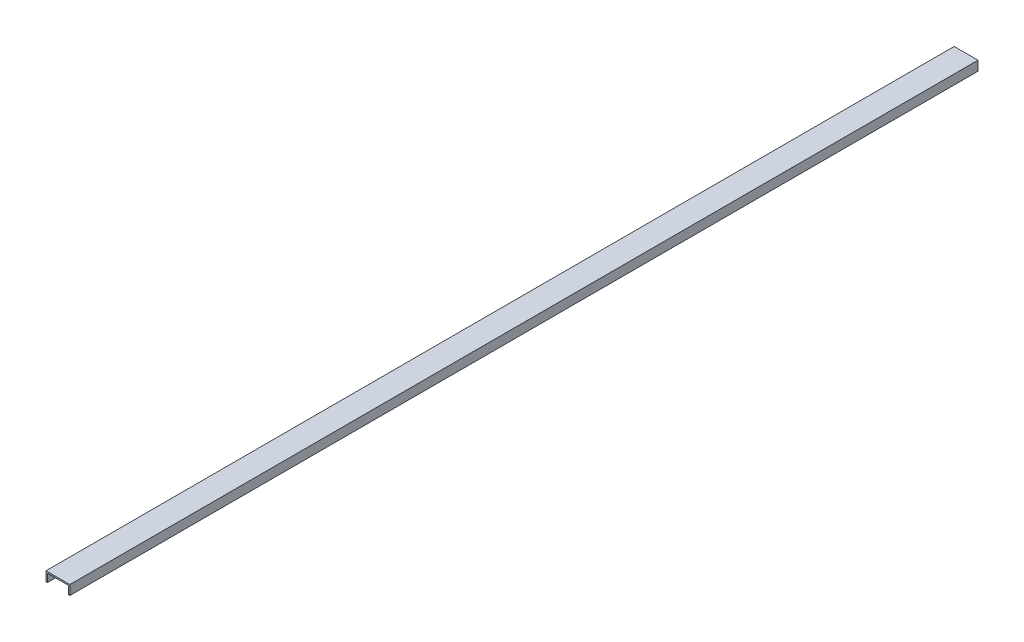
SolidWorks part; units mm, degrees
ref_plane "Front Plane" through (0, 0, 0) normal (0, 0, 1) x (1, 0, 0)
ref_plane "Top Plane" through (0, 0, 0) normal (0, 1, 0) x (1, 0, 0)
ref_plane "Right Plane" through (0, 0, 0) normal (1, 0, 0) x (0, 0, -1)
sketch "Sketch1" plane through (0, 0, 0) normal (0, 0, 1) x (1, 0, 0)
  line L0 (0, 0) -> (0, 20)
  line L1 (0, 20) -> (50, 20)
  line L2 (50, 20) -> (50, 0)
  line L3 (50, 0) -> (47, 0)
  line L4 (47, 0) -> (47, 17)
  line L5 (47, 17) -> (3, 17)
  line L6 (3, 17) -> (3, 0)
  line L7 (3, 0) -> (0, 0)
  dimension "D1" = 50
  dimension "D2" = 20
  dimension "D3" = 3
  dimension "D4" = 3
extrude "Boss-Extrude1" add sketch "Sketch1" along normal blind 1785
sketch "Sketch2" plane through (0, 0, 1785) normal (0, 0, 1) x (1, 0, 0)
  line L0 (0, 0) -> (0, 20)
  line L1 (0, 20) -> (50, 20)
  line L2 (50, 20) -> (50, 0)
  line L3 (50, 0) -> (47, 0)
  line L4 (47, 0) -> (47, 17)
  line L5 (47, 17) -> (3, 17)
  line L6 (3, 17) -> (3, 0)
  line L7 (3, 0) -> (0, 0)
extrude "R" add sketch "Sketch2" along normal blind 60
sketch "Sketch3" plane through (0, 0, 0) normal (0, 0, -1) x (-1, 0, 0)
  line L0 (-50, 0) -> (-50, 20)
  line L1 (-50, 20) -> (0, 20)
  line L2 (0, 20) -> (0, 0)
  line L3 (0, 0) -> (-3, 0)
  line L4 (-3, 0) -> (-3, 17)
  line L5 (-3, 17) -> (-47, 17)
  line L6 (-47, 17) -> (-47, 0)
  line L7 (-47, 0) -> (-50, 0)
extrude "L" add sketch "Sketch3" along normal blind 60
equation "\"boxWidth\"=1930.0"
equation "\"D1@Boss-Extrude1\"= \"boxWidth\" - 70 - 70 - 5"
equation "\"start\"=700.0"
equation "\"CarBeamWidth\"=700.0"
equation "\"WheelWidth\"=650.0"
equation "\"Wheel_FrontBoxDistance\"=1390.0"
equation "\"boxLength\"=5100.0"
equation "\"MetalSheet_3mm_length\"=5030.0"
equation "\"MetalSheet_3mm_width\"=1923.0"
equation "\"MetalSheet_3mm_FloorCut_L_length\"=1764.0"
equation "\"MetalSheet_3mm_FloorCut_L_disdance\"=1665.0"
equation "\"MetalSheet_3mm_FloorCut_R_length\"=1764.0"
equation "\"MetalSheet_3mm_FloorCut_R_disdance\"=1665.0"
equation "\"indoorHeight\"=1940.0"
equation "\"indoorHeight_para\"=25.0"
equation "\"rearLightHeight_para\"=265.0"
equation "\"doorColumnBar_A_FR_3mm_length_Cut\"=2310.0"
equation "\"A\"=0.0"
equation "\"haveDoor_R\"=1"
equation "\"side_door_bottom_R_3mm_length\"=1934.0"
equation "\"side_door_bottom_R_3mm_toFrontDistance\"=1583.0"
equation "\"1Bar_Side_RF_3mm_length\"=1493.0"
equation "\"1Bar_Side_RB_3mm_length\"=1493.0"
equation "\"DoorSeparator_RF_3mm_withHinge_toFrontDistance\"=1673.0"
equation "\"DoorSeparator_RF_3mm_withHinge_exist\"=1"
equation "\"DoorSeparator_RB_3mm_withHinge_toFrontDistance\"=3427.0"
equation "\"DoorSeparator_RB_3mm_withHinge_exist\"=1"
equation "\"Door_R1_L_open_Single_toFrontDistance\"=2547.5"
equation "\"Door_R1_L_open_Single_exist\"=1"
equation "\"door_base_long7_R1_L_open_Single_height\"=1890.0"
equation "\"door_base_short7_R1_L_open_Single_height\"=1890.0"
equation "\"door_base_short7_R1_L_open_Single_width\"=864"
equation "\"Door_R1_R_open_Single_toFrontDistance\"=3422.0"
equation "\"Door_R1_R_open_Single_exist\"=1"
equation "\"door_base_long7_R1_R_open_Single_height\"=1890.0"
equation "\"door_base_short7_R1_R_open_Single_height\"=1890.0"
equation "\"door_base_short7_R1_R_open_Single_width\"=864"
equation "\"x\"=66.0"
equation "\"door_base_double_BL_height\"=1890.0"
equation "\"door_base_short7_BL_Single_height\"=1890.0"
equation "\"door_base_short7_BL_Single_width\"=864"
equation "\"door_base_long7_BR_Single_height\"=1890.0"
equation "\"door_base_short7_BR_Single_height\"=1890.0"
equation "\"door_base_short7_BR_Single_width\"=864"
equation "\"da\"=62.0"
equation "\"SquareTube_length\"=1923.0"
equation "\"channelSteel_length\"=5030.0"
equation "\"SquareTube_inFront_AvgDistance\"=285.0"
equation "\"SquareTube_inFront_TotalCount\"=5"
equation "\"SquareTube_inFront1_cutDepth50_R\"=0.5"
equation "\"SquareTube_inFront1_cutDepth50_L\"=0.5"
equation "\"SquareTube_inFront2_cutDepth50_R\"=0.5"
equation "\"SquareTube_inFront2_cutDepth50_L\"=0.5"
equation "\"SquareTube_inFront3_cutDepth50_R\"=0.5"
equation "\"SquareTube_inFront3_cutDepth50_L\"=0.5"
equation "\"SquareTube_inFront4_cutDepth50_R\"=0.5"
equation "\"SquareTube_inFront4_cutDepth50_L\"=0.5"
equation "\"SquareTube_inFront5_cutDepth50_R\"=50"
equation "\"SquareTube_inFront5_cutDepth50_L\"=50"
equation "\"SquareTube_inFront6_cutDepth50_R\"=50"
equation "\"SquareTube_inFront6_cutDepth50_L\"=50"
equation "\"SquareTube_inFront7_cutDepth50_R\"=50"
equation "\"SquareTube_inFront7_cutDepth50_L\"=50"
equation "\"SquareTube_inFront8_cutDepth50_R\"=50"
equation "\"SquareTube_inFront8_cutDepth50_L\"=50"
equation "\"SquareTube_inFront9_cutDepth50_R\"=50"
equation "\"SquareTube_inFront9_cutDepth50_L\"=50"
equation "\"SquareTube_inFront10_cutDepth50_R\"=50"
equation "\"SquareTube_inFront10_cutDepth50_L\"=50"
equation "\"SquareTube_inFront11_cutDepth50_R\"=50"
equation "\"SquareTube_inFront11_cutDepth50_L\"=50"
equation "\"SquareTube_inFront12_cutDepth50_R\"=50"
equation "\"SquareTube_inFront12_cutDepth50_L\"=50"
equation "\"SquareTube_inFront13_cutDepth50_R\"=50"
equation "\"SquareTube_inFront13_cutDepth50_L\"=50"
equation "\"SquareTube_inFront14_cutDepth50_R\"=50"
equation "\"SquareTube_inFront14_cutDepth50_L\"=50"
equation "\"SquareTube_inBack_AvgDistance\"=333.125"
equation "\"SquareTube_inBack_TotalCount\"=9"
equation "\"SquareTube_inBack1_cutDepth50_R\"=50"
equation "\"SquareTube_inBack1_cutDepth50_L\"=50"
equation "\"SquareTube_inBack2_cutDepth50_R\"=50"
equation "\"SquareTube_inBack2_cutDepth50_L\"=50"
equation "\"SquareTube_inBack3_cutDepth50_R\"=50"
equation "\"SquareTube_inBack3_cutDepth50_L\"=50"
equation "\"SquareTube_inBack4_cutDepth50_R\"=50"
equation "\"SquareTube_inBack4_cutDepth50_L\"=50"
equation "\"SquareTube_inBack5_cutDepth50_R\"=50"
equation "\"SquareTube_inBack5_cutDepth50_L\"=50"
equation "\"SquareTube_inBack6_cutDepth50_R\"=0.5"
equation "\"SquareTube_inBack6_cutDepth50_L\"=0.5"
equation "\"SquareTube_inBack7_cutDepth50_R\"=0.5"
equation "\"SquareTube_inBack7_cutDepth50_L\"=0.5"
equation "\"SquareTube_inBack8_cutDepth50_R\"=0.5"
equation "\"SquareTube_inBack8_cutDepth50_L\"=0.5"
equation "\"doorColumnBar_A_FL_3mm_length_Cut\"=2310.0"
equation "\"B\"=0.0"
equation "\"haveDoor_L\"=1"
equation "\"side_door_bottom_L_3mm_length\"=1934.0"
equation "\"side_door_bottom_L_3mm_toFrontDistance\"=1583.0"
equation "\"1Bar_Side_LF_3mm_length\"=1493.0"
equation "\"1Bar_Side_LB_3mm_length\"=1493.0"
equation "\"DoorSeparator_LF_3mm_withHinge_toFrontDistance\"=1673.0"
equation "\"DoorSeparator_LF_3mm_withHinge_exist\"=1"
equation "\"DoorSeparator_LB_3mm_withHinge_toFrontDistance\"=3427.0"
equation "\"DoorSeparator_LB_3mm_withHinge_exist\"=1"
equation "\"Door_L1_L_open_Single_toFrontDistance\"=3422.0"
equation "\"Door_L1_L_open_Single_exist\"=1"
equation "\"door_base_long7_L1_L_open_Single_height\"=1890.0"
equation "\"door_base_short7_L1_L_open_Single_height\"=1890.0"
equation "\"door_base_short7_L1_L_open_Single_width\"=864"
equation "\"Door_L1_R_open_Single_toFrontDistance\"=2547.5"
equation "\"Door_L1_R_open_Single_exist\"=1"
equation "\"door_base_long7_L1_R_open_Single_height\"=1890.0"
equation "\"door_base_short7_L1_R_open_Single_height\"=1890.0"
equation "\"door_base_short7_L1_R_open_Single_width\"=864"
equation "\"D1@R\" = IIF (  ( \"haveDoor_R\" )  = 1 , 60 , 70 ) "
equation "\"D1@L\" = IIF (  ( \"haveDoor_L\" )  = 1 , 60 , 70 ) "
